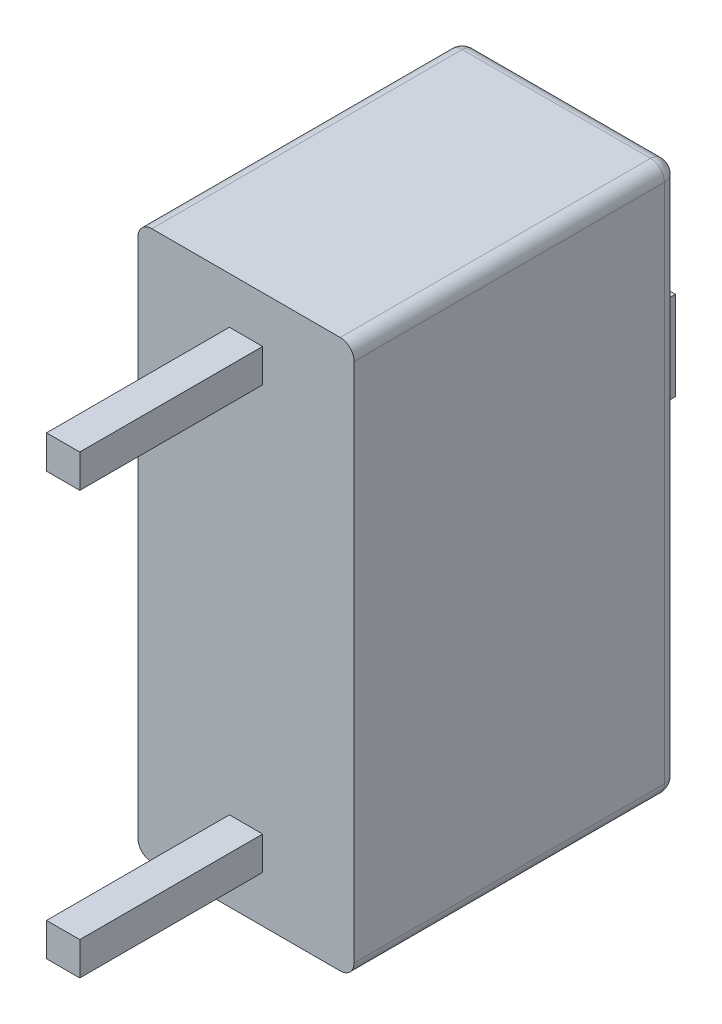
SolidWorks part; units mm, degrees
ref_plane "Ön Düzlem" through (0, 0, 0) normal (0, 0, 1) x (1, 0, 0)
ref_plane "Üst Düzlem" through (0, 0, 0) normal (0, 1, 0) x (1, 0, 0)
ref_plane "Sağ Düzlem" through (0, 0, 0) normal (1, 0, 0) x (0, 0, -1)
sketch "Çizim1" plane through (0, 0, 0) normal (0, 0, 1) x (1, 0, 0)
  line L1 (-1.95, 4.95) -> (1.95, 4.95)
  line L2 (-1.95, 4.95) -> (-1.95, -4.95)
  line L3 (-1.95, -4.95) -> (1.95, -4.95)
  line L4 (1.95, 4.95) -> (1.95, -4.95)
  line L5 (-1.95, 4.95) -> (1.95, -4.95) construction
  line L6 (-1.95, -4.95) -> (1.95, 4.95) construction
  point P0 (0, 0)
extrude "Yükseklik-Ekstrüzyon1" add sketch "Çizim1" along normal blind 5.85
sketch "Çizim3" plane through (0, 0, 0) normal (0, 0, -1) x (-1, 0, 0)
  line L7 (-0.7, 1.6) -> (0.7, 1.6)
  line L8 (-0.7, 1.6) -> (-0.7, -1.6)
  line L9 (-0.7, -1.6) -> (0.7, -1.6)
  line L10 (0.7, 1.6) -> (0.7, -1.6)
  line L11 (-0.7, 1.6) -> (0.7, -1.6) construction
  line L12 (-0.7, -1.6) -> (0.7, 1.6) construction
  point P13 (0, 0)
extrude "Kes-Ekstrüzyon1" cut sketch "Çizim3" against normal blind 1
sketch "Çizim4" plane through (0, 0, 1) normal (0, 0, -1) x (-1, 0, 0)
  line L0 (0.7, 1.6) -> (0.7, 0)
  line L1 (0.7, -1.6) -> (0.7, 1.6) construction
  line L2 (0.7, 0) -> (-0.7, 0)
  line L3 (-0.7, 1.6) -> (-0.7, -1.6) construction
  line L4 (-0.7, 0) -> (-0.7, 1.6)
  line L5 (-0.7, 1.6) -> (0.7, 1.6)
extrude "Yükseklik-Ekstrüzyon2" add sketch "Çizim4" along normal blind 2.2 separate body
sketch "Çizim5" plane through (0, 0, 1) normal (0, 0, -1) x (-1, 0, 0)
  line L1 (0.7, 0) -> (-0.7, 0)
  line L2 (0.7, 0) -> (0.7, -1.6)
  line L3 (0.7, -1.6) -> (-0.7, -1.6)
  line L4 (-0.7, 0) -> (-0.7, -1.6)
extrude "Yükseklik-Ekstrüzyon3" add sketch "Çizim5" along normal blind 0.9 separate body
fillet "Radyus1" radius 0.25 8 edges at (0, -4.95, 0) (-1.95, 0, 0) (0, 4.95, 0) (1.95, 0, 0) (1.95, 4.95, 2.925) (-1.95, 4.95, 2.925) (1.95, -4.95, 2.925) (-1.95, -4.95, 2.925)
sketch "Çizim6" plane through (0, 0, 5.85) normal (0, 0, 1) x (1, 0, 0)
  line L2 (0.3, 4.11) -> (-0.3, 4.11)
  line L3 (0.3, 4.11) -> (0.3, 3.51)
  line L4 (0.3, 3.51) -> (-0.3, 3.51)
  line L5 (-0.3, 4.11) -> (-0.3, 3.51)
  line L6 (0.3, 4.11) -> (-0.3, 3.51) construction
  line L7 (0.3, 3.51) -> (-0.3, 4.11) construction
  line L8 (0.3, -3.51) -> (-0.3, -3.51)
  line L9 (0.3, -3.51) -> (0.3, -4.11)
  line L10 (0.3, -4.11) -> (-0.3, -4.11)
  line L11 (-0.3, -3.51) -> (-0.3, -4.11)
  line L12 (0.3, -3.51) -> (-0.3, -4.11) construction
  line L13 (0.3, -4.11) -> (-0.3, -3.51) construction
  point P1 (0, -3.81)
  point P2 (0, 3.81)
  point P4 (0, 0)
extrude "Yükseklik-Ekstrüzyon4" add sketch "Çizim6" along normal blind 3.3
